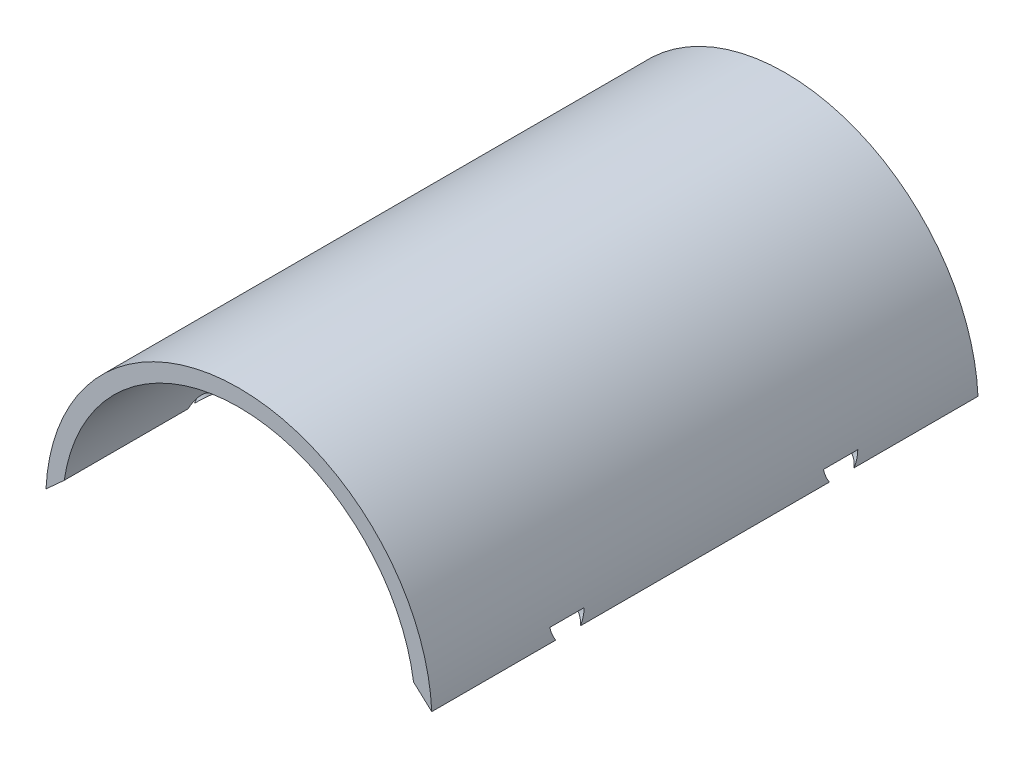
SolidWorks part; units mm, degrees
ref_plane "Front Plane" through (0, 0, 0) normal (0, 0, 1) x (1, 0, 0)
ref_plane "Top Plane" through (0, 0, 0) normal (0, 1, 0) x (1, 0, 0)
ref_plane "Right Plane" through (0, 0, 0) normal (1, 0, 0) x (0, 0, -1)
sketch "Sketch1" plane through (0, 0, 0) normal (0, 0, 1) x (1, 0, 0)
  line L0 (0, 0) -> (0, 44.45) construction
  line L1 (-40.2039, 5.9378) -> (40.2039, 5.9378) construction
  line L2 (-44.399, 2.1278) -> (44.399, 2.1278) construction
  line L3 (-40.2039, 5.9378) -> (-44.399, 2.1278)
  line L4 (40.2039, 5.9378) -> (44.399, 2.1278)
  arc A0 (44.399, 2.1278) -> (-44.399, 2.1278) centre (0, 0) ccw
  arc A1 (40.2039, 5.9378) -> (-40.2039, 5.9378) centre (0, 0) ccw
  dimension "D1" = 88.9
  dimension "D2" = 3.81
  dimension "D3" = 3.81
extrude "Boss-Extrude1" add sketch "Sketch1" along normal blind 125.73
sketch "Sketch2" plane through (-21.1272, 23.263, 0) normal (0.6723, -0.7403, 0) x (0.7403, 0.6723, 0)
  line L0 (-28.6033, 125.73) -> (-28.6033, 0) construction
  line L1 (-31.4368, 125.73) -> (-25.7698, 125.73) construction
  line L2 (-31.4368, 0) -> (-25.7698, 0) construction
  line L3 (-31.4368, 62.865) -> (-25.7698, 62.865) construction
  line L4 (-31.4368, 125.73) -> (-31.4368, 0) construction
  line L5 (-25.7698, 125.73) -> (-25.7698, 0) construction
  circle A0 centre (-28.6033, 94.361) radius 4
  circle A1 centre (-28.6033, 31.369) radius 4
  dimension "D1" = 8
  dimension "D2" = 31.496
extrude "Cut-Extrude1" cut sketch "Sketch2" against normal blind 2
sketch "Sketch3" plane through (21.1272, 23.263, 0) normal (-0.6723, -0.7403, 0) x (-0.7403, 0.6723, 0)
  line L0 (-28.6033, -125.73) -> (-28.6033, 0) construction
  line L1 (-25.7698, -125.73) -> (-31.4368, -125.73) construction
  line L2 (-25.7698, 0) -> (-31.4368, 0) construction
  line L3 (-25.7698, -62.865) -> (-31.4368, -62.865) construction
  line L4 (-25.7698, -125.73) -> (-25.7698, 0) construction
  line L5 (-31.4368, -125.73) -> (-31.4368, 0) construction
  circle A0 centre (-28.6033, -94.361) radius 4
  circle A1 centre (-28.6033, -31.369) radius 4
  dimension "D1" = 8
  dimension "D2" = 31.496
extrude "Cut-Extrude2" cut sketch "Sketch3" against normal blind 2.032
